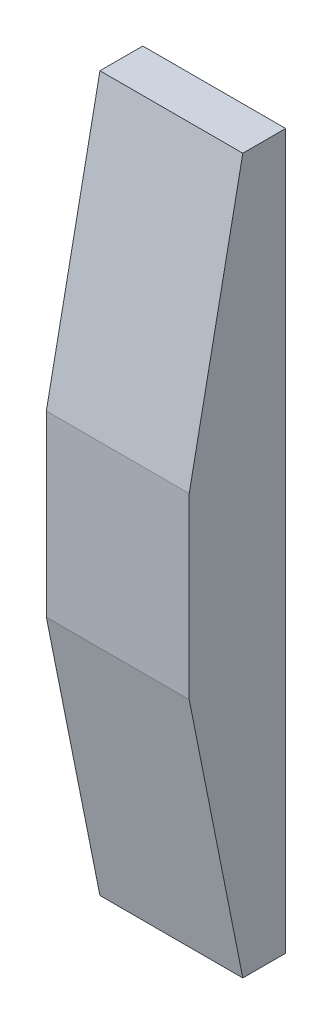
SolidWorks part; units mm, degrees
ref_plane "Front Plane" through (0, 0, 0) normal (0, 0, 1) x (1, 0, 0)
ref_plane "Top Plane" through (0, 0, 0) normal (0, 1, 0) x (1, 0, 0)
ref_plane "Right Plane" through (0, 0, 0) normal (1, 0, 0) x (0, 0, -1)
sketch "Sketch3" plane through (-1220, 0, 0) normal (-1, 0, 0) x (0, 0, 1)
  line L0 (0, 500) -> (75, 125)
  line L1 (0, 610) -> (0, -610) construction
  line L2 (75, 125) -> (75, -125)
  line L3 (75, -125) -> (0, -500)
  line L4 (0, 500) -> (0, -500)
  point P6 (0, 0)
  point P7 (0, 0)
  point P8 (75, 0)
  dimension "D1" = 75
  dimension "D2" = 250
  dimension "D3" = 1000
extrude "Boss-Extrude1" add sketch "Sketch3" against normal blind 200
sketch "Sketch4" plane through (0, 0, 0) normal (0, 0, -1) x (-1, 0, 0)
  line L4 (1220, -500) -> (1220, 500)
  line L5 (1220, 500) -> (1020, 500)
  line L6 (1020, 500) -> (1020, -500)
  line L7 (1020, -500) -> (1220, -500)
  line L8 (1220, -500) -> (1220, 500)
  line L9 (1220, 500) -> (1020, 500)
  line L10 (1020, 500) -> (1020, -500)
  line L11 (1020, -500) -> (1220, -500)
  dimension "D1" = 0
extrude "Boss-Extrude2" add sketch "Sketch4" along normal blind 60
